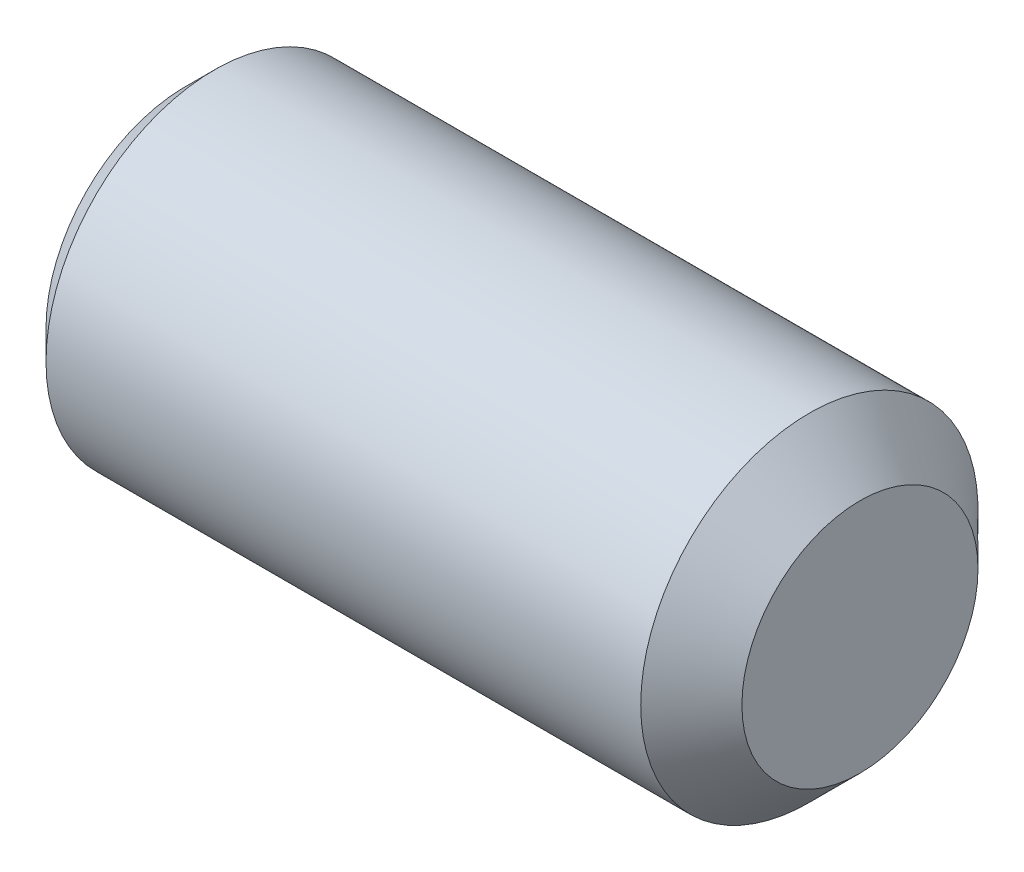
SolidWorks part; units mm, degrees
ref_plane "Front" through (0, 0, 0) normal (0, 0, 1) x (1, 0, 0)
ref_plane "Top" through (0, 0, 0) normal (0, 1, 0) x (1, 0, 0)
ref_plane "Right" through (0, 0, 0) normal (1, 0, 0) x (0, 0, -1)
other "Configuration Table"
sketch "Sketch1" plane through (0, 0, 0) normal (0, 0, 1) x (1, 0, 0)
  line L0 (0, 0) -> (10, 0)
  line L1 (10, 0) -> (10, 1.75)
  line L2 (10, 1.75) -> (9.25, 2.5)
  line L3 (9.25, 2.5) -> (0.433, 2.5)
  line L4 (0.433, 2.5) -> (0, 2.067)
  line L5 (0, 2.067) -> (0, 0)
  line L6 (-10.745, 0) -> (0.8952, 0) construction
  dimension "l" = 10
  dimension "dp" = 3.5
  dimension "d" = 5
  dimension "df" = 4.134
  dimension "D2" = 45
  dimension "D1" = 45
revolve "Base" add sketch "Sketch1" angle 360 about L6
cosmetic thread "ThreadCosmetic1" [suppressed] parameters "D2"=4.134
sketch "Sketch2" plane through (0, -0.0219, 0.0101) normal (-1, 0, 0) x (0, 0, 1)
  line L1 (1.4332, 0.0219) -> (0.7115, 1.2719)
  line L2 (0.7115, 1.2719) -> (-0.7318, 1.2719)
  line L3 (-0.7318, 1.2719) -> (-1.4535, 0.0219)
  line L4 (-1.4535, 0.0219) -> (-0.7318, -1.2281)
  line L5 (-0.7318, -1.2281) -> (0.7115, -1.2281)
  line L6 (0.7115, -1.2281) -> (1.4332, 0.0219)
  circle A0 centre (-0.0101, 0.0219) radius 1.25 construction
  dimension "s" = 2.5
extrude "HexagonSocket" cut sketch "Sketch2" against normal blind 2
sketch "Sketch3" plane through (0, 0, 0) normal (0, 0, 1) x (1, 0, 0)
  line L0 (-3.1441, 0) -> (0.1622, 0) construction
  line L2 (2, 1.25) -> (2.7217, 0)
  line L4 (2, 1.25) -> (2, 0)
  line L5 (2, 0) -> (2.7217, 0)
  dimension "D1" = 60
revolve "Cut-Revolve1" cut sketch "Sketch3" angle 360 about L0
sketch "Sketch4" plane through (0, 0, 0) normal (0, 0, 1) x (1, 0, 0)
  line L0 (0.433, 2.125) -> (0.6495, 2.5)
  line L1 (0.6495, 2.5) -> (0.6495, 2.933)
  line L2 (0.6495, 2.933) -> (0.2165, 2.933)
  line L3 (0.2165, 2.933) -> (0.2165, 2.5)
  line L4 (0.2165, 2.5) -> (0.433, 2.125)
  line L5 (0, 0) -> (0.9616, 0) construction
  line L6 (0.433, 2.5) -> (0.433, -2.5) construction
  dimension "D1" = 5
  dimension "D2" = 0.433
revolve "Cut-Revolve10" [suppressed] cut sketch "Sketch4" angle 360 about L5
pattern_linear "LPattern10" [suppressed] count 18 spacing 0.5196 along (1, 0, 0)
equation "\"df@Sketch1\" = \"D2@ThreadCosmetic1\""
equation "\"D1@Sketch4\" = \"d@Sketch1\""
equation "\"D2@Sketch4\" =  ( \"d@Sketch1\" - \"D2@ThreadCosmetic1\" )  / 2"
equation "\"D3@LPattern10\" = \"D2@Sketch4\" * 1.2"
equation "\"D1@LPattern10\" = (  \"l@Sketch1\" -  ( \"d@Sketch1\" - \"df@Sketch1\" )  / 2 )  / \"D3@LPattern10\""
